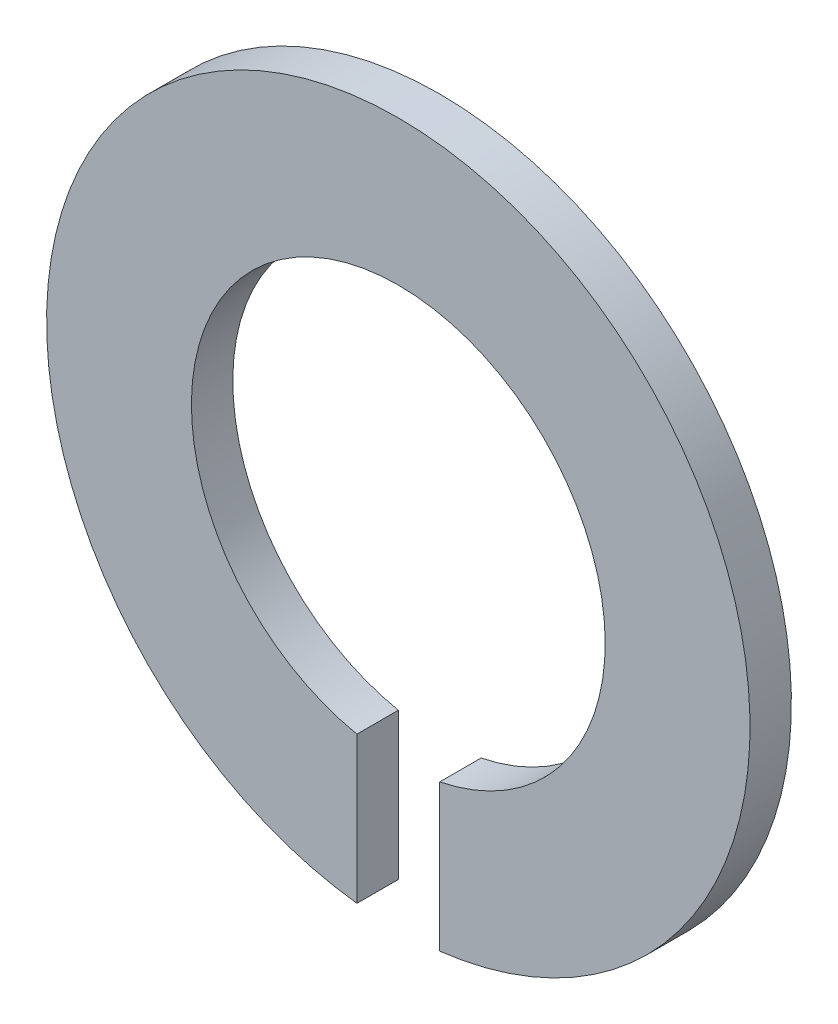
SolidWorks part; units mm, degrees
ref_plane "Plan de face" through (0, 0, 0) normal (0, 0, 1) x (1, 0, 0)
ref_plane "Plan de dessus" through (0, 0, 0) normal (0, 1, 0) x (1, 0, 0)
ref_plane "Plan de droite" through (0, 0, 0) normal (1, 0, 0) x (0, 0, -1)
sketch "Esquisse2" plane through (0, 0, 0) normal (0, 0, 1) x (1, 0, 0)
  line L0 (0, 0) -> (0, -4.3237) construction
  line L1 (0.5, -4.2205) -> (0.5, -2.4495)
  line L2 (-0.5, -4.2205) -> (-0.5, -2.4495)
  arc A0 (0.5, -2.4495) -> (-0.5, -2.4495) centre (0, 0) ccw
  arc A1 (0.5, -4.2205) -> (-0.5, -4.2205) centre (0, 0) ccw
  dimension "D1" = 5
  dimension "D2" = 8.5
  dimension "D3" = 0.5
extrude "Boss.-Extru.1" add sketch "Esquisse2" along normal blind 0.5
